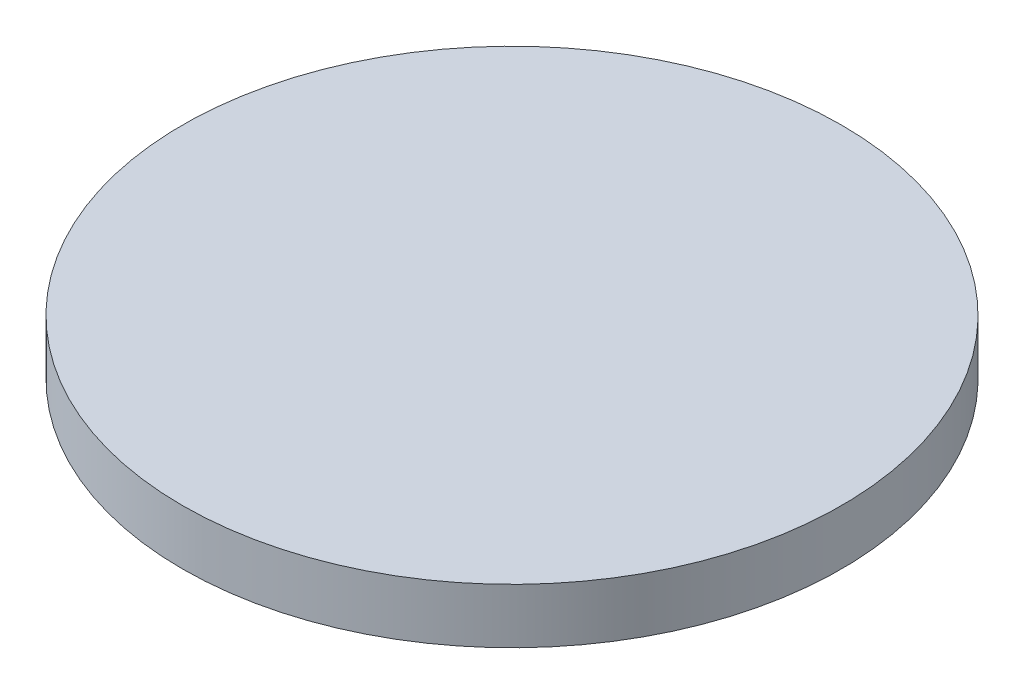
SolidWorks part; units mm, degrees
ref_plane "Front Plane" through (0, 0, 0) normal (0, 0, 1) x (1, 0, 0)
ref_plane "Top Plane" through (0, 0, 0) normal (0, 1, 0) x (1, 0, 0)
ref_plane "Right Plane" through (0, 0, 0) normal (1, 0, 0) x (0, 0, -1)
sketch "Sketch1" plane through (0, 0, 0) normal (0, 1, 0) x (1, 0, 0)
  circle A0 centre (0, 0) radius 15
  dimension "D1" = 30
extrude "Boss-Extrude1" add sketch "Sketch1" along normal blind 2.5
